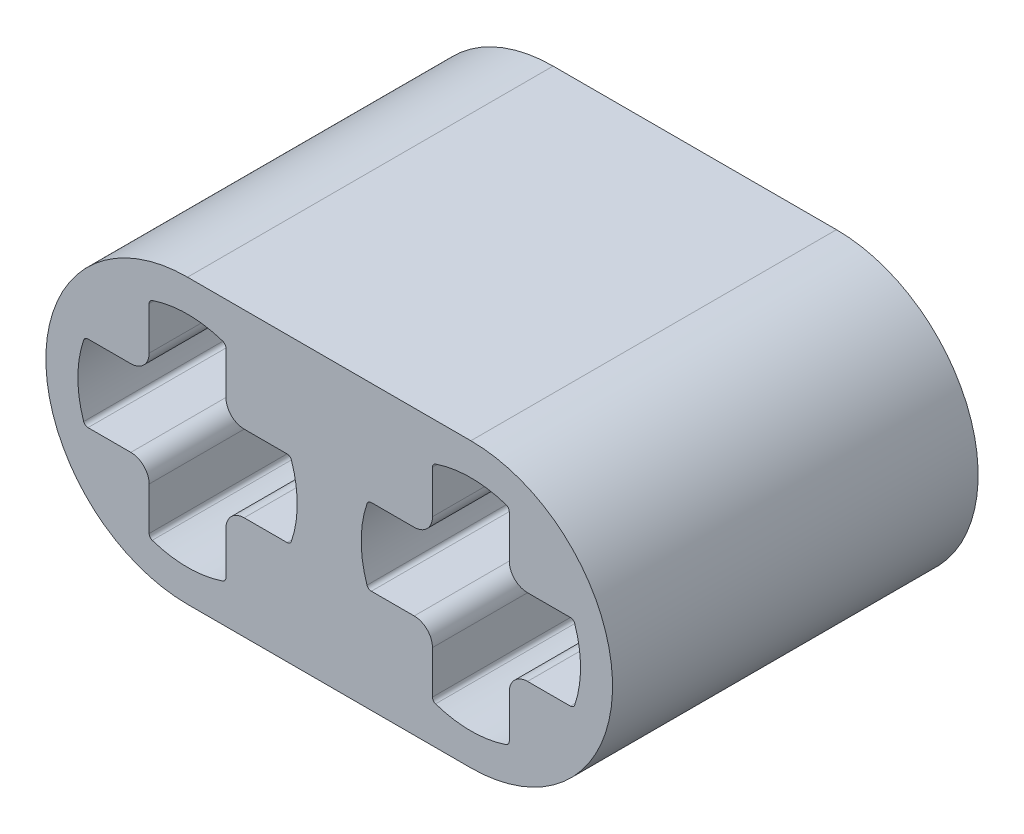
SolidWorks part; units mm, degrees
ref_plane "Front Plane" through (0, 0, 0) normal (0, 0, 1) x (1, 0, 0)
ref_plane "Top Plane" through (0, 0, 0) normal (0, 1, 0) x (1, 0, 0)
ref_plane "Right Plane" through (0, 0, 0) normal (1, 0, 0) x (0, 0, -1)
sketch "Sketch2" plane through (0, 0, 0) normal (0, 0, 1) x (1, 0, 0)
  line L0 (-3.1, 3.1) -> (3.1, 3.1)
  line L1 (-3.1, 0) -> (3.1, 0) construction
  line L2 (-3.1, -3.1) -> (3.1, -3.1)
  arc A0 (-3.1, 3.1) -> (-3.1, -3.1) centre (-3.1, 0) ccw
  arc A1 (3.1, -3.1) -> (3.1, 3.1) centre (3.1, 0) ccw
  dimension "D2" = 6.2
  dimension "D3" = 6.2
  dimension "D1" = 6.2
  dimension "D4" = 6.2
  dimension "D5" = 6.2
extrude "Boss-Extrude1" add sketch "Sketch2" against normal blind 8
sketch "Sketch4" plane through (0, 0, 0) normal (0, 0, 1) x (1, 0, 0)
  line L0 (-3.94, -0.84) -> (-3.94, -2.2482)
  line L2 (-3.94, 2.2482) -> (-3.94, 0.84)
  line L4 (-2.26, 2.2482) -> (-2.26, 0.84)
  line L5 (-3.94, 2.2482) -> (-2.26, -2.2482) construction
  line L6 (-3.94, -2.2482) -> (-2.26, 2.2482) construction
  line L7 (-0.8518, 0.84) -> (-2.26, 0.84)
  line L9 (-0.8518, -0.84) -> (-2.26, -0.84)
  line L11 (-0.8518, 0.84) -> (-5.3482, -0.84) construction
  line L12 (-0.8518, -0.84) -> (-5.3482, 0.84) construction
  line L17 (-3.94, 0.84) -> (-5.3482, 0.84)
  line L18 (-3.94, -0.84) -> (-5.3482, -0.84)
  line L19 (-2.26, -0.84) -> (-2.26, -2.2482)
  arc A0 (-2.26, 2.2482) -> (-3.94, 2.2482) centre (-3.1, 0) ccw
  arc A2 (-5.3482, 0.84) -> (-5.3482, -0.84) centre (-3.1, 0) ccw
  arc A3 (-3.94, -2.2482) -> (-2.26, -2.2482) centre (-3.1, 0) ccw
  arc A4 (-0.8518, -0.84) -> (-0.8518, 0.84) centre (-3.1, 0) ccw
  dimension "D1" = 4.8
  dimension "D3" = 1.68
  dimension "D4" = 1.68
extrude "Cut-Extrude1" cut sketch "Sketch4" against normal through all contours A0 L2 L17 A2 L18 L0 A3 L19 L9 A4 L7 L4
fillet "Fillet1" radius 0.4 1 edges at (-3.94, -0.84, -4)
fillet "Fillet2" radius 0.4 1 edges at (-3.94, 0.84, -4)
fillet "Fillet3" radius 0.4 1 edges at (-2.26, 0.84, -4)
fillet "Fillet4" radius 0.4 1 edges at (-2.26, -0.84, -4)
fillet "Fillet5" radius 0.1 1 edges at (-3.94, -2.2482, -4)
fillet "Fillet6" radius 0.1 1 edges at (-2.26, -2.2482, -4)
fillet "Fillet7" radius 0.1 1 edges at (-0.8518, 0.84, -4)
fillet "Fillet8" radius 0.1 1 edges at (-0.8518, -0.84, -4)
fillet "Fillet9" radius 0.1 1 edges at (-2.26, 2.2482, -4)
fillet "Fillet10" radius 0.1 1 edges at (-3.94, 2.2482, -4)
fillet "Fillet11" radius 0.1 1 edges at (-5.3482, 0.84, -4)
fillet "Fillet12" radius 0.1 1 edges at (-5.3482, -0.84, -4)
mirror "Mirror1" about plane through (0, 0, 0) normal (1, 0, 0) of "Cut-Extrude1", "Fillet1", "Fillet2", "Fillet3", "Fillet4", "Fillet5", "Fillet6", "Fillet7", "Fillet8", "Fillet9", "Fillet10", "Fillet11", "Fillet12"
